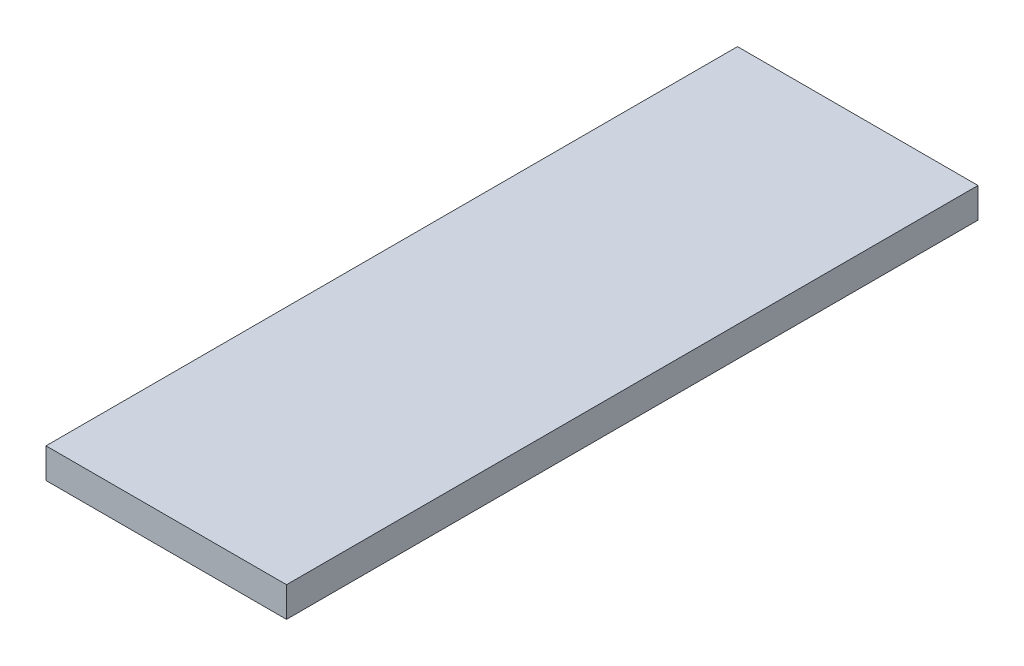
SolidWorks part; units mm, degrees
material "Beech"
ref_plane "Front Plane" through (0, 0, 0) normal (0, 0, 1) x (1, 0, 0)
ref_plane "Top Plane" through (0, 0, 0) normal (0, 1, 0) x (1, 0, 0)
ref_plane "Right Plane" through (0, 0, 0) normal (1, 0, 0) x (0, 0, -1)
sketch "Sketch1" plane through (0, 0, 0) normal (0, 1, 0) x (1, 0, 0)
  line L1 (0, 0) -> (304.8, 0)
  line L2 (0, 0) -> (0, 304.8)
  line L3 (0, 304.8) -> (304.8, 304.8)
  line L4 (304.8, 0) -> (304.8, 304.8)
  dimension "D1" = 304.8
  dimension "D2" = 304.8
extrude "Boss-Extrude1" add sketch "Sketch1" along normal blind 6.35
sketch "Sketch2" plane through (0, 6.35, 0) normal (0, 1, 0) x (1, 0, 0)
  line L1 (304.8, 304.8) -> (0, 304.8) construction
  line L2 (50.8, 304.8) -> (50.8, 158.75)
  line L3 (50.8, 158.75) -> (0, 158.75)
  line L4 (0, 304.8) -> (0, 0) construction
  line L6 (0, 158.75) -> (0, 0)
  line L7 (0, 0) -> (304.8, 0)
  line L8 (304.8, 0) -> (304.8, 304.8)
  line L9 (304.8, 304.8) -> (50.8, 304.8)
  dimension "D1" = 50.8
  dimension "D2" = 146.05
extrude "Cut-Extrude2" cut sketch "Sketch2" against normal blind 6.35 contours L3 L6 L7 L8 L9 L2
